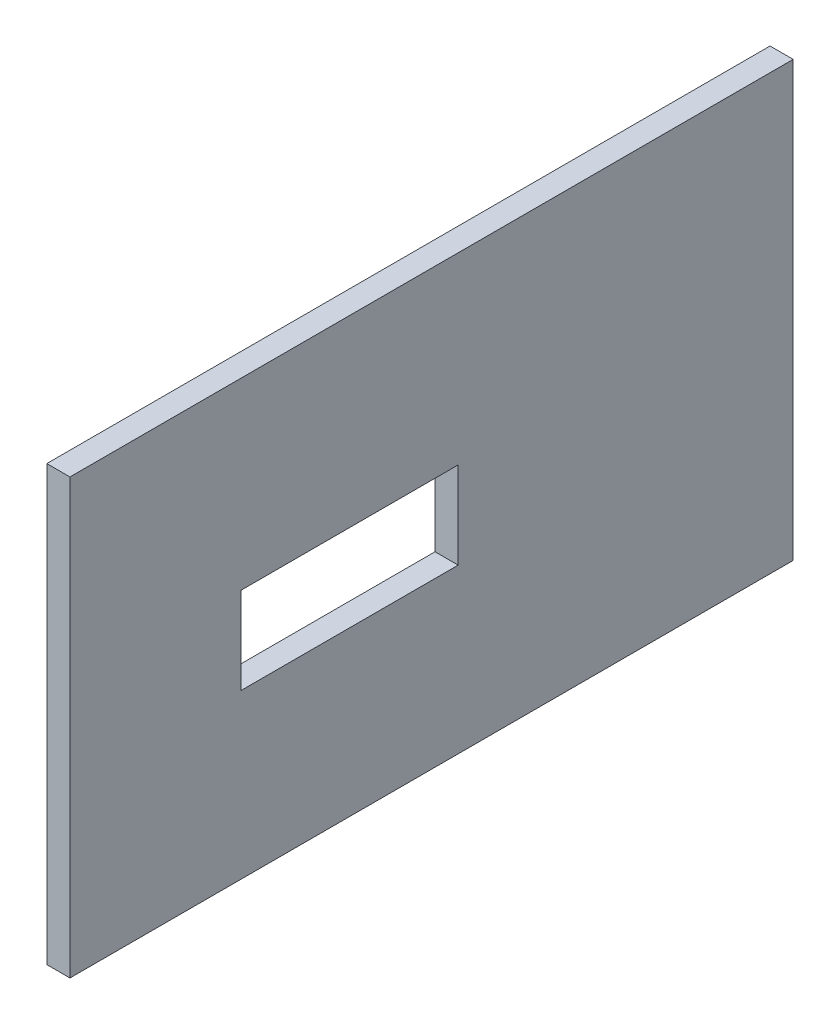
SolidWorks part; units mm, degrees
ref_plane "Front Plane" through (0, 0, 0) normal (0, 0, 1) x (1, 0, 0)
ref_plane "Top Plane" through (0, 0, 0) normal (0, 1, 0) x (1, 0, 0)
ref_plane "Right Plane" through (0, 0, 0) normal (1, 0, 0) x (0, 0, -1)
sketch "Sketch2" plane through (0, 0, 0) normal (1, 0, 0) x (0, 0, -1)
  line L1 (-101.0636, 37.4) -> (-1.0636, 37.4)
  line L2 (-101.0636, 37.4) -> (-101.0636, -22.6)
  line L3 (-101.0636, -22.6) -> (-1.0636, -22.6)
  line L4 (-1.0636, 37.4) -> (-1.0636, -22.6)
  line L5 (-101.0636, 37.4) -> (-1.0636, -22.6) construction
  line L6 (-101.0636, -22.6) -> (-1.0636, 37.4) construction
  point P0 (-51.0636, 7.4)
  dimension "D1" = 60
  dimension "D2" = 100
extrude "Boss-Extrude1" add sketch "Sketch2" along normal blind 3.2
sketch "Sketch3" plane through (3.2, 0, 0) normal (1, 0, 0) x (0, 0, -1)
  line L1 (-77.3877, 12) -> (-47.3877, 12)
  line L2 (-77.3877, 12) -> (-77.3877, 0)
  line L3 (-77.3877, 0) -> (-47.3877, 0)
  line L4 (-47.3877, 12) -> (-47.3877, 0)
  line L5 (-77.3877, 12) -> (-47.3877, 0) construction
  line L6 (-77.3877, 0) -> (-47.3877, 12) construction
  point P0 (-62.3877, 6)
  dimension "D1" = 30
  dimension "D2" = 12
extrude "Cut-Extrude1" cut sketch "Sketch3" against normal blind 3.2
sketch "Sketch4" plane through (3.2, 0, 0) normal (1, 0, 0) x (0, 0, -1)
  line L0 (-85.4045, -22.6) -> (-85.4045, 37.4)
  line L1 (-101.0636, -22.6) -> (-1.0636, -22.6) construction
  line L2 (-1.0636, 37.4) -> (-101.0636, 37.4) construction
  line L3 (-85.4045, -22.6) -> (-85.4045, 37.4) construction
